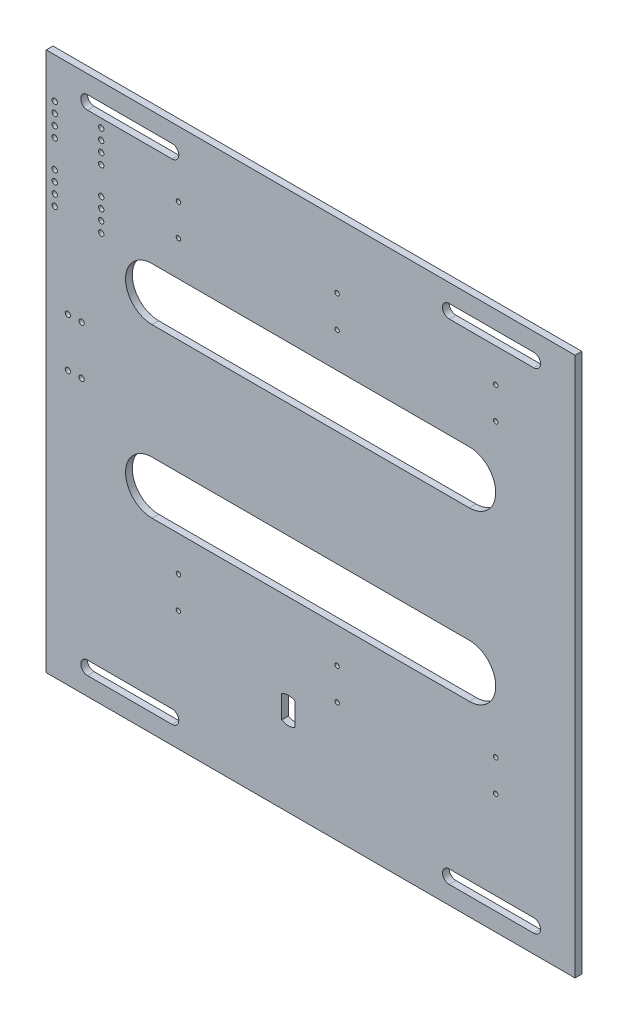
SolidWorks part; units mm, degrees
ref_plane "Alzado" through (0, 0, 0) normal (0, 0, 1) x (1, 0, 0)
ref_plane "Planta" through (0, 0, 0) normal (0, 1, 0) x (1, 0, 0)
ref_plane "Vista lateral" through (0, 0, 0) normal (1, 0, 0) x (0, 0, -1)
sketch "Croquis1" plane through (0, 0, 0) normal (0, 0, 1) x (1, 0, 0)
  line L1 (-250, -255) -> (250, -255)
  line L2 (-250, -255) -> (-250, 255)
  line L3 (-250, 255) -> (250, 255)
  line L4 (250, -255) -> (250, 255)
  line L5 (-250, -255) -> (250, 255) construction
  line L6 (-250, 255) -> (250, -255) construction
  point P0 (0, 0)
  dimension "D1" = 500
  dimension "D2" = 510
extrude "Saliente-Extruir1" add sketch "Croquis1" along normal blind 6.35
sketch "Croquis2" plane through (0, 0, 6.35) normal (0, 0, 1) x (1, 0, 0)
  line L0 (0, 255) -> (0, -255) construction
  line L1 (250, 255) -> (-250, 255) construction
  line L2 (-250, -255) -> (250, -255) construction
  line L3 (-250, 0) -> (250, 0) construction
  line L4 (-250, 255) -> (-250, -255) construction
  line L5 (250, -255) -> (250, 255) construction
  line L6 (-211, -231.5) -> (-131, -231.5) construction
  line L7 (-171, -231.5) -> (171, -231.5) construction
  line L8 (-171, -231.5) -> (-171, 231.5) construction
  line L9 (-171, 231.5) -> (171, 231.5) construction
  line L10 (171, -231.5) -> (171, 231.5) construction
  line L11 (-171, -231.5) -> (171, 231.5) construction
  line L12 (-171, 231.5) -> (171, -231.5) construction
  line L13 (-211, -225.15) -> (-131, -225.15)
  line L14 (-211, -237.85) -> (-131, -237.85)
  line L15 (-211, 231.5) -> (-131, 231.5) construction
  line L16 (-211, 237.85) -> (-131, 237.85)
  line L17 (-211, 225.15) -> (-131, 225.15)
  line L18 (131, 231.5) -> (211, 231.5) construction
  line L19 (131, 237.85) -> (211, 237.85)
  line L20 (131, 225.15) -> (211, 225.15)
  line L21 (131, -231.5) -> (211, -231.5) construction
  line L22 (131, -225.15) -> (211, -225.15)
  line L23 (131, -237.85) -> (211, -237.85)
  line L24 (-14.65, -160.733) -> (-14.65, -182.267)
  line L25 (-27.35, -160.733) -> (-27.35, -182.267)
  line L26 (-27.35, -171.5) -> (-14.65, -171.5) construction
  arc A0 (-211, -225.15) -> (-211, -237.85) centre (-211, -231.5) ccw
  arc A1 (-131, -237.85) -> (-131, -225.15) centre (-131, -231.5) ccw
  arc A2 (-211, 237.85) -> (-211, 225.15) centre (-211, 231.5) ccw
  arc A3 (-131, 225.15) -> (-131, 237.85) centre (-131, 231.5) ccw
  arc A4 (131, 237.85) -> (131, 225.15) centre (131, 231.5) ccw
  arc A5 (211, 225.15) -> (211, 237.85) centre (211, 231.5) ccw
  arc A6 (131, -225.15) -> (131, -237.85) centre (131, -231.5) ccw
  arc A7 (211, -237.85) -> (211, -225.15) centre (211, -231.5) ccw
  arc A8 (-14.65, -160.733) -> (-27.35, -160.733) centre (-21, -171.5) ccw
  arc A9 (-27.35, -182.267) -> (-14.65, -182.267) centre (-21, -171.5) ccw
  point P12 (0, 0)
  point P20 (-171, -231.5)
  point P27 (-171, 231.5)
  point P34 (171, 231.5)
  point P41 (171, -231.5)
  point P54 (-21, -171.5)
  dimension "D11" = 426.5
  dimension "D12" = 271
  dimension "D13" = 25
  dimension "D1" = 342
  dimension "D2" = 463
  dimension "D3" = 12.7
  dimension "D4" = 80
  dimension "D5" = 80
  dimension "D6" = 12.7
  dimension "D7" = 80
  dimension "D8" = 12.7
  dimension "D9" = 12.7
  dimension "D10" = 80
  dimension "D14" = 12.7
extrude "Cortar-Extruir1" cut sketch "Croquis2" against normal through all
sketch "Croquis4" plane through (0, 0, 6.35) normal (0, 0, 1) x (1, 0, 0)
  line L0 (-150, 105) -> (150, 105) construction
  line L1 (-150, 130) -> (150, 130)
  line L2 (-150, 80) -> (150, 80)
  line L3 (-150, -53.46) -> (150, -53.46) construction
  line L4 (-150, -28.46) -> (150, -28.46)
  line L5 (-150, -78.46) -> (150, -78.46)
  line L6 (250, 255) -> (-250, 255) construction
  line L7 (250, -255) -> (250, 255) construction
  line L8 (-250, 255) -> (-250, -255) construction
  arc A0 (-150, 130) -> (-150, 80) centre (-150, 105) ccw
  arc A1 (150, 80) -> (150, 130) centre (150, 105) ccw
  arc A2 (-150, -28.46) -> (-150, -78.46) centre (-150, -53.46) ccw
  arc A3 (150, -78.46) -> (150, -28.46) centre (150, -53.46) ccw
  point P2 (0, 105)
  point P8 (0, -53.46)
  dimension "D3" = 100
  dimension "D4" = 100
  dimension "D1" = 50
  dimension "D2" = 158.46
  dimension "D5" = 150
extrude "Cortar-Extruir2" cut sketch "Croquis4" against normal through all
sketch "Croquis5" plane through (0, 0, 6.35) normal (0, 0, 1) x (1, 0, 0)
  line L0 (-250, 255) -> (-250, -255) construction
  line L1 (250, 255) -> (-250, 255) construction
  point P0 (-242, 217)
  point P1 (-198, 217)
  point P2 (-242, 161)
  point P3 (-198, 161)
  dimension "D1" = 8
  dimension "D2" = 44
  dimension "D3" = 38
  dimension "D4" = 56
hole_wizard "Taladro roscado M6x1.01" positions "Croquis6" profile "Croquis7" tap size "M6x1.0" standard "Ansi Metric"
sketch "Croquis6" plane through (0, 0, 6.35) normal (0, 0, 1) x (1, 0, 0)
  point P0 (-242, 217)
  point P3 (-198, 217)
  point P6 (-198, 161)
  point P9 (-242, 161)
sketch "Croquis7" plane through (-242, 217, 6.35) normal (1, 0, 0) x (0, -1, 0)
  line L0 (0, 0) -> (0, 18.5022)
  line L1 (0, 18.5022) -> (2.5, 17)
  line L2 (2.5, 17) -> (2.5, 0)
  line L5 (2.5, 0) -> (0, 0)
  line L10 (0, 18.5022) -> (-2.5, 17) construction
  line L11 (0, -6.35) -> (0, 107.95) construction
  dimension "Diámetro de perforador para roscar" = 5
  dimension "Profundidad de perforador para roscar" = 17
  dimension "Ángulo de perforador" = 118
cosmetic thread "Rosca de taladro1" parameters "D1"=6.35, "D2"=6
cosmetic thread "Rosca de taladro2" parameters "D1"=6.35, "D2"=6
cosmetic thread "Rosca de taladro3" parameters "D1"=6.35, "D2"=6
cosmetic thread "Rosca de taladro4" parameters "D1"=6.35, "D2"=6
pattern_linear "MatrizL1" count 4 spacing 10 along (0, -1, 0) of "Taladro roscado M6x1.01"
sketch "Croquis12" plane through (0, 0, 6.35) normal (0, 0, 1) x (1, 0, 0)
  point P0 (-125, 193.27)
  point P1 (-125, 163.27)
  point P3 (25, 193.27)
  point P5 (25, 163.27)
  point P7 (175, 193.27)
  point P9 (175, 163.27)
  point P11 (-125, -141.73)
  point P13 (-125, -111.73)
  point P15 (25, -111.73)
  point P17 (25, -141.73)
  point P19 (175, -111.73)
  point P21 (175, -141.73)
hole_wizard "Taladro roscado M5x0.82" positions "Croquis13" profile "Croquis14" tap size "M5x0.8" standard "Ansi Metric" end condition up to next
sketch "Croquis13" plane through (0, 0, 6.35) normal (0, 0, 1) x (1, 0, 0)
  point P0 (-125, 193.27)
  point P3 (-125, 163.27)
  point P6 (25, 193.27)
  point P9 (25, 163.27)
  point P12 (175, 193.27)
  point P15 (175, 163.27)
  point P18 (175, -111.73)
  point P21 (175, -141.73)
  point P24 (25, -111.73)
  point P27 (25, -141.73)
  point P30 (-125, -111.73)
  point P33 (-125, -141.73)
sketch "Croquis14" plane through (-125, 193.27, 6.35) normal (1, 0, 0) x (0, -1, 0)
  line L0 (0, 0) -> (0, 6.35)
  line L1 (0, 6.35) -> (2.1, 6.35)
  line L2 (2.1, 6.35) -> (2.1, 0)
  line L5 (2.1, 0) -> (0, 0)
  line L11 (0, -6.35) -> (0, 107.95) construction
  dimension "Diámetro de perforador para roscar hasta el siguiente" = 4.2
  dimension "Profundidad de perforador para roscar hasta el siguiente" = 6.35
cosmetic thread "Rosca de taladro17" parameters "D2"=5
cosmetic thread "Rosca de taladro18" parameters "D2"=5
cosmetic thread "Rosca de taladro19" parameters "D2"=5
cosmetic thread "Rosca de taladro20" parameters "D2"=5
cosmetic thread "Rosca de taladro21" parameters "D2"=5
cosmetic thread "Rosca de taladro22" parameters "D2"=5
cosmetic thread "Rosca de taladro23" parameters "D2"=5
cosmetic thread "Rosca de taladro24" parameters "D2"=5
cosmetic thread "Rosca de taladro25" parameters "D2"=5
cosmetic thread "Rosca de taladro26" parameters "D2"=5
cosmetic thread "Rosca de taladro27" parameters "D2"=5
cosmetic thread "Rosca de taladro28" parameters "D2"=5
sketch "Croquis15" plane through (0, 0, 6.35) normal (0, 0, 1) x (1, 0, 0)
  point P0 (-216.5427, 48.77)
  point P1 (-229.5427, 48.77)
  point P3 (-216.5427, 2.77)
  point P5 (-229.5427, 2.77)
hole_wizard "Taladro roscado M6x1.02" positions "Croquis16" profile "Croquis17" tap size "M6x1.0" standard "Ansi Metric" end condition up to next
sketch "Croquis16" plane through (0, 0, 6.35) normal (0, 0, 1) x (1, 0, 0)
  point P0 (-229.5427, 48.77)
  point P3 (-216.5427, 48.77)
  point P6 (-216.5427, 2.77)
  point P9 (-229.5427, 2.77)
sketch "Croquis17" plane through (-229.5427, 48.77, 6.35) normal (1, 0, 0) x (0, -1, 0)
  line L0 (0, 0) -> (0, 6.35)
  line L1 (0, 6.35) -> (2.5, 6.35)
  line L2 (2.5, 6.35) -> (2.5, 0)
  line L5 (2.5, 0) -> (0, 0)
  line L11 (0, -6.35) -> (0, 107.95) construction
  dimension "Diámetro de perforador para roscar hasta el siguiente" = 5
  dimension "Profundidad de perforador para roscar hasta el siguiente" = 6.35
cosmetic thread "Rosca de taladro29" parameters "D2"=6
cosmetic thread "Rosca de taladro30" parameters "D2"=6
cosmetic thread "Rosca de taladro31" parameters "D2"=6
cosmetic thread "Rosca de taladro32" parameters "D2"=6
